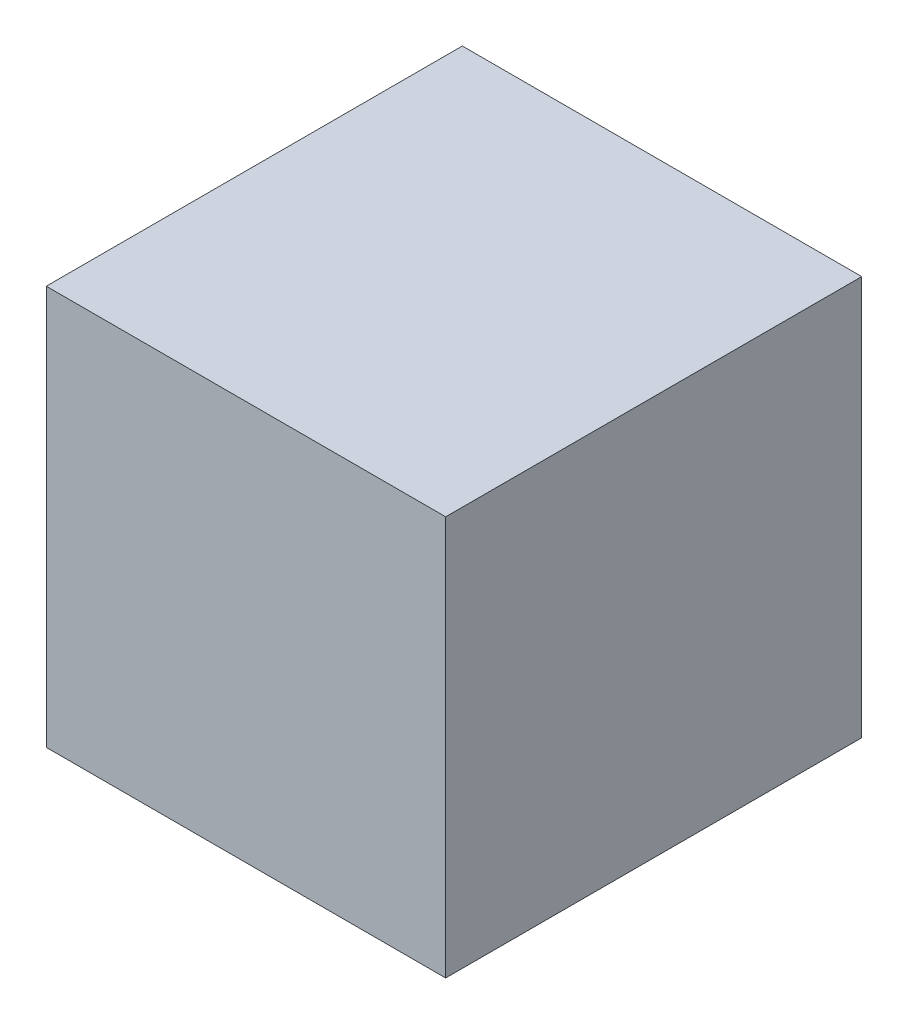
SolidWorks part; units mm, degrees
ref_plane "Alzado" through (0, 0, 0) normal (0, 0, 1) x (1, 0, 0)
ref_plane "Planta" through (0, 0, 0) normal (0, 1, 0) x (1, 0, 0)
ref_plane "Vista lateral" through (0, 0, 0) normal (1, 0, 0) x (0, 0, -1)
sketch "Croquis1" plane through (0, 0, 0) normal (0, 0, 1) x (1, 0, 0)
  line L1 (-24, 24) -> (24, 24)
  line L2 (-24, 24) -> (-24, -24)
  line L3 (-24, -24) -> (24, -24)
  line L4 (24, 24) -> (24, -24)
  line L5 (-24, 24) -> (24, -24) construction
  line L6 (-24, -24) -> (24, 24) construction
  point P0 (0, 0)
  dimension "D1" = 48
  dimension "D2" = 48
extrude "Saliente-Extruir1" add sketch "Croquis1" along normal blind 50
sketch "Croquis3" plane through (-24, 0, 0) normal (-1, 0, 0) x (0, 0, 1)
  line L0 (50, 24) -> (50, -24) construction
  circle A0 centre (26, 0) radius 5
  dimension "D1" = 10
  dimension "D2" = 24
extrude "Cortar-Extruir2" cut sketch "Croquis3" against normal blind 10
